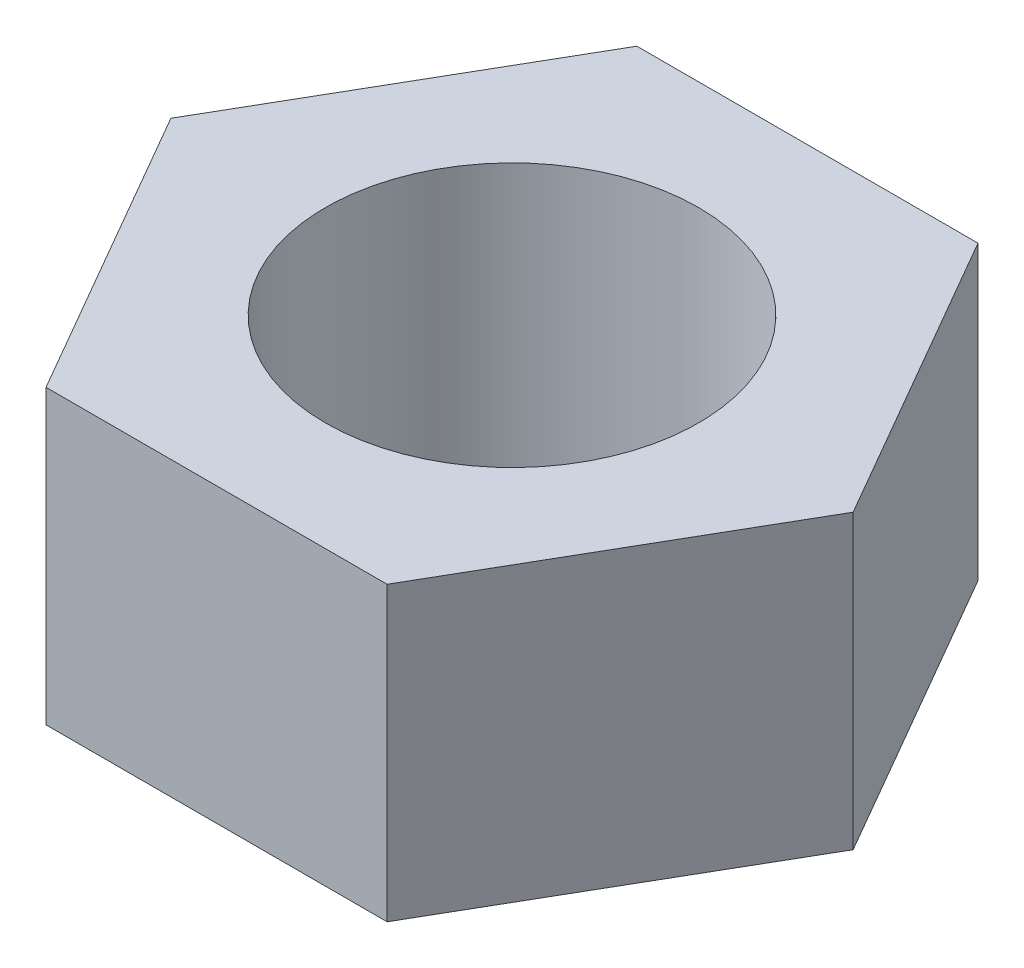
SolidWorks part; units mm, degrees
ref_plane "Front Plane" through (0, 0, 0) normal (0, 0, 1) x (1, 0, 0)
ref_plane "Top Plane" through (0, 0, 0) normal (0, 1, 0) x (1, 0, 0)
ref_plane "Right Plane" through (0, 0, 0) normal (1, 0, 0) x (0, 0, -1)
sketch "Sketch1" plane through (0, 0, 0) normal (0, 1, 0) x (1, 0, 0)
  line L13 (0, 12.5) -> (0.1674, 12.5)
  line L14 (0, 0) -> (-40.6762, 0) construction
  line L15 (5.4848, 9.5) -> (-5.4848, 9.5)
  line L16 (-5.4848, 9.5) -> (-10.9697, 0)
  line L17 (-10.9697, 0) -> (-5.4848, -9.5)
  line L18 (-5.4848, -9.5) -> (5.4848, -9.5)
  line L19 (5.4848, -9.5) -> (10.9697, 0)
  line L20 (10.9697, 0) -> (5.4848, 9.5)
  circle A1 centre (0, 0) radius 6
  point P13 (0, 0)
  dimension "D1" = 19
  dimension "D2" = 12
extrude "Boss-Extrude1" add sketch "Sketch1" along normal blind 9.4
